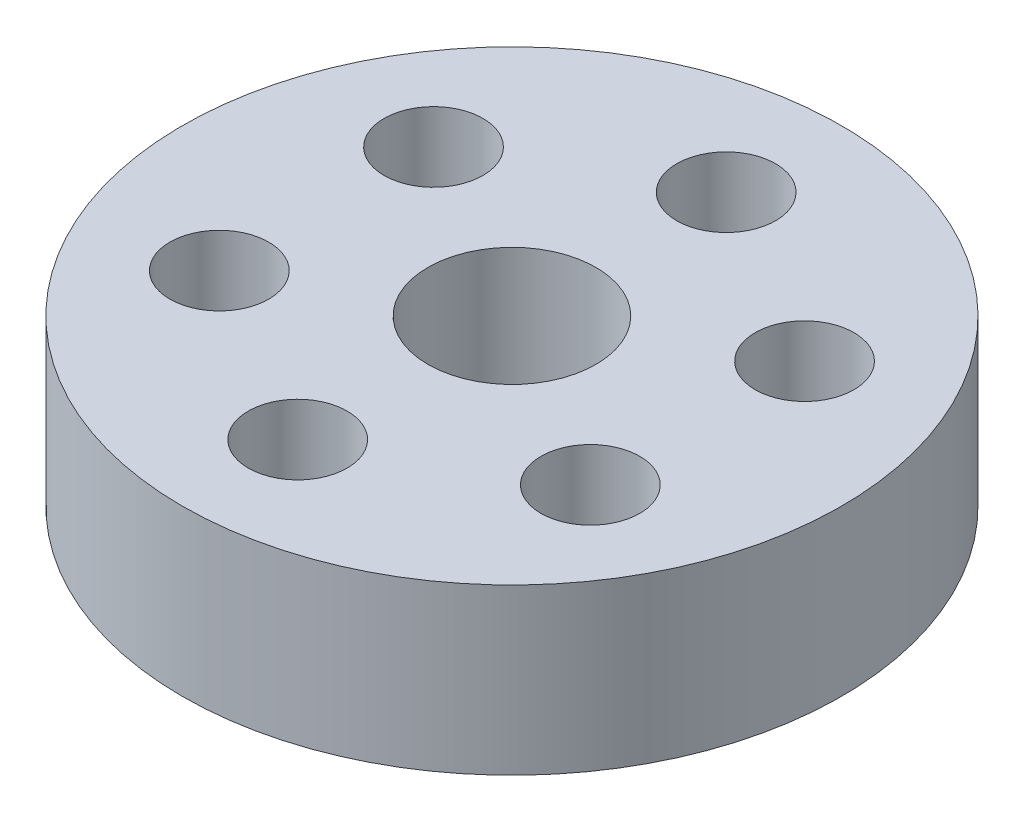
SolidWorks part; units mm, degrees
ref_plane "Front Plane" through (0, 0, 0) normal (0, 0, 1) x (1, 0, 0)
ref_plane "Top Plane" through (0, 0, 0) normal (0, 1, 0) x (1, 0, 0)
ref_plane "Right Plane" through (0, 0, 0) normal (1, 0, 0) x (0, 0, -1)
sketch "Sketch1" plane through (0, 0, 0) normal (0, 1, 0) x (1, 0, 0)
  line L0 (0, 0) -> (0, 8.255) construction
  line L1 (0, 0) -> (7.149, 4.1275) construction
  line L2 (0, 0) -> (7.149, -4.1275) construction
  line L3 (0, 0) -> (0, -8.255) construction
  line L4 (0, 0) -> (-7.149, -4.1275) construction
  line L5 (0, 0) -> (-7.149, 4.1275) construction
  circle A0 centre (0, 0) radius 12.7
  circle A1 centre (0, 8.255) radius 1.905
  circle A2 centre (0, 0) radius 3.2385
  circle A3 centre (7.149, 4.1275) radius 1.905
  circle A4 centre (7.149, -4.1275) radius 1.905
  circle A5 centre (0, -8.255) radius 1.905
  circle A6 centre (-7.149, -4.1275) radius 1.905
  circle A7 centre (-7.149, 4.1275) radius 1.905
  point P18 (0, 0)
  dimension "D1" = 25.4
  dimension "D2" = 3.81
  dimension "D4" = 6.477
  dimension "D3" = 8.255
  dimension "D5" = 6
extrude "base" add sketch "Sketch1" along normal blind 6.35
